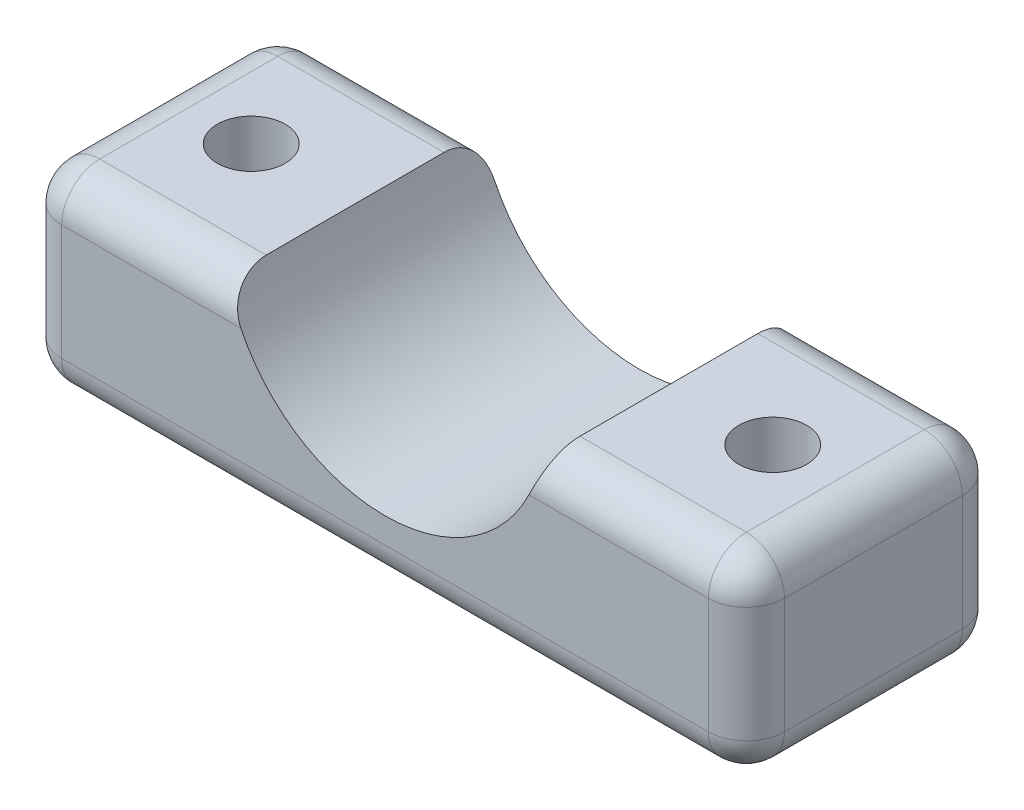
SolidWorks part; units mm, degrees
material "PLA ABS"
ref_plane "Front Plane" through (0, 0, 0) normal (0, 0, 1) x (1, 0, 0)
ref_plane "Top Plane" through (0, 0, 0) normal (0, 1, 0) x (1, 0, 0)
ref_plane "Right Plane" through (0, 0, 0) normal (1, 0, 0) x (0, 0, -1)
sketch "Sketch1" plane through (0, 0, 0) normal (0, 0, 1) x (1, 0, 0)
  line L0 (16.002, 22.352) -> (36.1315, 22.352)
  line L1 (-36.1315, 0) -> (36.1315, 0)
  line L2 (-36.1315, 0) -> (-36.1315, 22.352)
  line L3 (-36.1315, 22.352) -> (-16.002, 22.352)
  line L4 (36.1315, 0) -> (36.1315, 22.352)
  arc A0 (-16.002, 22.352) -> (16.002, 22.352) centre (0, 22.352) ccw
  dimension "D1" = 32.004
  dimension "D2" = 72.263
  dimension "D3" = 6.35
extrude "Boss-Extrude1" add sketch "Sketch1" along normal mid plane 25.4
sketch "Sketch2" plane through (0, 22.352, 0) normal (0, 1, 0) x (1, 0, 0)
  line L0 (-26.0668, 12.7) -> (-26.0667, -12.7) construction
  line L1 (-16.002, 12.7) -> (-36.1315, 12.7) construction
  line L2 (-16.002, -12.7) -> (-36.1315, -12.7) construction
  line L3 (0, 0) -> (0, 12.7) construction
  line L4 (16.002, 12.7) -> (-16.002, 12.7) construction
  circle A0 centre (-26.0668, 0) radius 3.3909
  circle A1 centre (26.0668, 0) radius 3.3909
  dimension "D1" = 6.7818
extrude "Cut-Extrude1" cut sketch "Sketch2" against normal through all
sketch "Sketch3" plane through (0, 0, 12.7) normal (0, 0, 1) x (1, 0, 0)
  line L0 (-16.002, 22.352) -> (-36.1315, 22.352) construction
  line L1 (-36.1315, 26.3528) -> (36.1315, 26.3528)
  line L2 (-36.1315, 26.3528) -> (-36.1315, 19.177)
  line L3 (-36.1315, 19.177) -> (36.1315, 19.177)
  line L4 (36.1315, 26.3528) -> (36.1315, 19.177)
  line L5 (-36.1315, 22.352) -> (-36.1315, 0) construction
  line L6 (36.1315, 0) -> (36.1315, 22.352) construction
  dimension "D1" = 3.175
extrude "Cut-Extrude2" cut sketch "Sketch3" against normal through all
sketch "Sketch6" plane through (0, 0, 0) normal (0, -1, 0) x (1, 0, 0)
  line L1 (-26.0667, -6.5625) -> (-20.3835, -3.2812)
  line L2 (-20.3835, -3.2812) -> (-20.3835, 3.2812)
  line L3 (-20.3835, 3.2812) -> (-26.0668, 6.5625)
  line L4 (-26.0668, 6.5625) -> (-31.75, 3.2812)
  line L5 (-31.75, 3.2812) -> (-31.75, -3.2812)
  line L6 (-31.75, -3.2812) -> (-26.0667, -6.5625)
  line L7 (26.0667, 6.5625) -> (20.3835, 3.2812)
  line L8 (20.3835, 3.2812) -> (20.3835, -3.2812)
  line L9 (20.3835, -3.2812) -> (26.0668, -6.5625)
  line L10 (26.0668, -6.5625) -> (31.75, -3.2812)
  line L11 (31.75, -3.2812) -> (31.75, 3.2812)
  line L12 (31.75, 3.2812) -> (26.0667, 6.5625)
  circle A0 centre (-26.0668, 0) radius 5.6833 construction
  circle A1 centre (26.0668, 0) radius 5.6833 construction
  dimension "D1" = 11.3665
extrude "Cut-Extrude3" cut sketch "Sketch6" against normal blind 4.0716
fillet "Fillet3" radius 3.81 14 edges at (-36.1315, 0, 0) (-36.1315, 9.5885, -12.7) (-36.1315, 19.177, 0) (-36.1315, 9.5885, 12.7) (36.1315, 0, 0) (36.1315, 9.5885, 12.7) (36.1315, 19.177, 0) (36.1315, 9.5885, -12.7) (-25.9077, 19.177, 12.7) (25.9077, 19.177, 12.7) (0, 0, 12.7) (0, 0, -12.7) (25.9077, 19.177, -12.7) (-25.9077, 19.177, -12.7)
